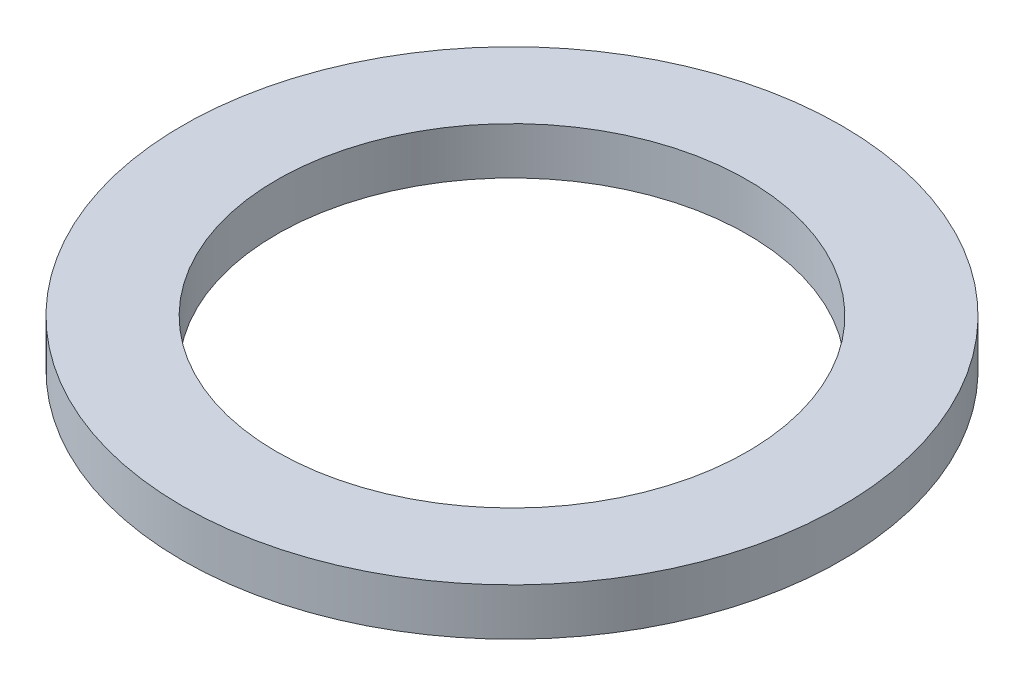
SolidWorks part; units mm, degrees
material "Plain Carbon Steel"
ref_plane "Front Plane" through (0, 0, 0) normal (0, 0, 1) x (1, 0, 0)
ref_plane "Top Plane" through (0, 0, 0) normal (0, 1, 0) x (1, 0, 0)
ref_plane "Right Plane" through (0, 0, 0) normal (1, 0, 0) x (0, 0, -1)
sketch "Sketch1" plane through (0, 0, 0) normal (0, 1, 0) x (1, 0, 0)
  circle A0 centre (0, 0) radius 25
  circle A1 centre (0, 0) radius 35
  dimension "D1" = 50
  dimension "D2" = 70
extrude "Boss-Extrude1" add sketch "Sketch1" along normal blind 5
